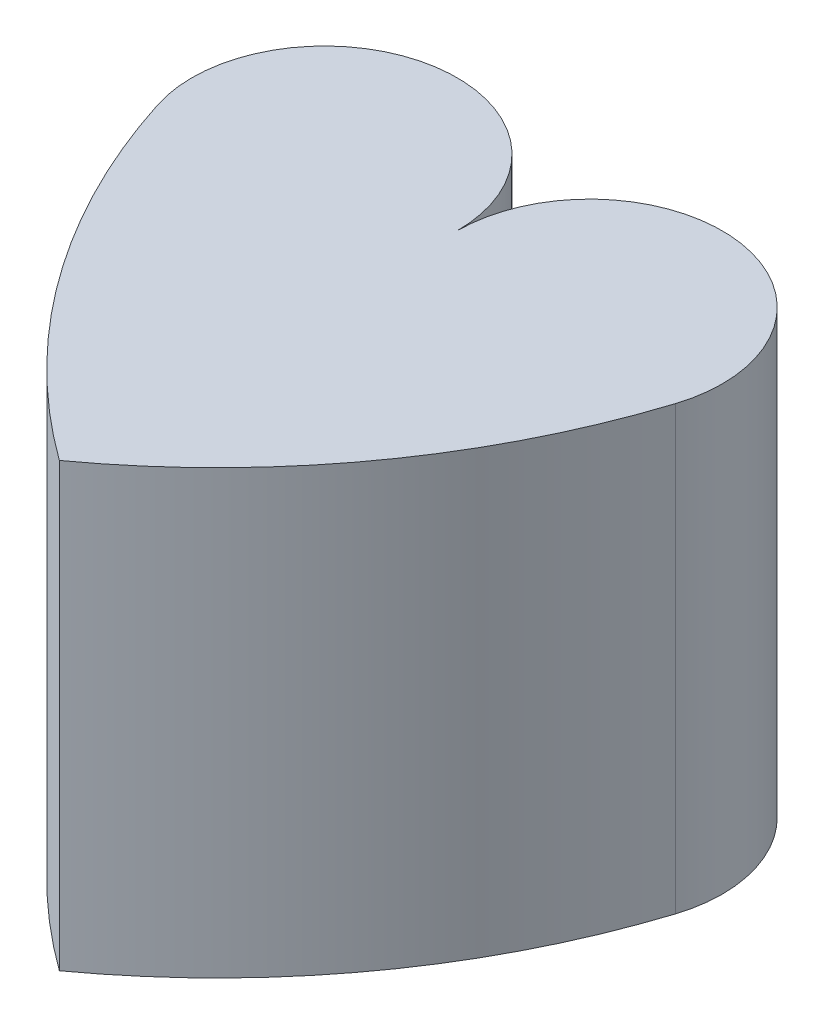
SolidWorks part; units mm, degrees
ref_plane "Front Plane" through (0, 0, 0) normal (0, 0, 1) x (1, 0, 0)
ref_plane "Top Plane" through (0, 0, 0) normal (0, 1, 0) x (1, 0, 0)
ref_plane "Right Plane" through (0, 0, 0) normal (1, 0, 0) x (0, 0, -1)
sketch "Sketch1" plane through (0, 0, 0) normal (0, 1, 0) x (1, 0, 0)
  line L0 (0, -55) -> (0, 55) construction
  line L1 (-3, 3) -> (3, 3) construction
  line L2 (-3, 3) -> (-3, -3) construction
  line L3 (-3, -3) -> (3, -3) construction
  line L4 (3, 3) -> (3, -3) construction
  line L5 (-3, 3) -> (3, -3) construction
  line L6 (-3, -3) -> (3, 3) construction
  line L7 (3, 0) -> (0, 3) construction
  line L8 (0, 3) -> (-3, 0) construction
  line L9 (-3, 0) -> (0, -3) construction
  line L10 (0, -3) -> (3, 0) construction
  circle A0 centre (0, 0) radius 2.1213 construction
  arc A1 (2.9287, 1.043) -> (0, 1.5) centre (1.5, 1.5) ccw
  arc A2 (0, 1.5) -> (-2.9287, 1.043) centre (-1.5, 1.5) ccw
  arc A3 (-2.9287, 1.043) -> (0, -3) centre (4.691, 3.4803) ccw
  arc A4 (2.9287, 1.043) -> (0, -3) centre (-4.691, 3.4803) cw
  point P0 (0, 0)
  dimension "D2" = 8
  dimension "D1" = 6
extrude "Boss-Extrude1" add sketch "Sketch1" along normal mid plane 5
